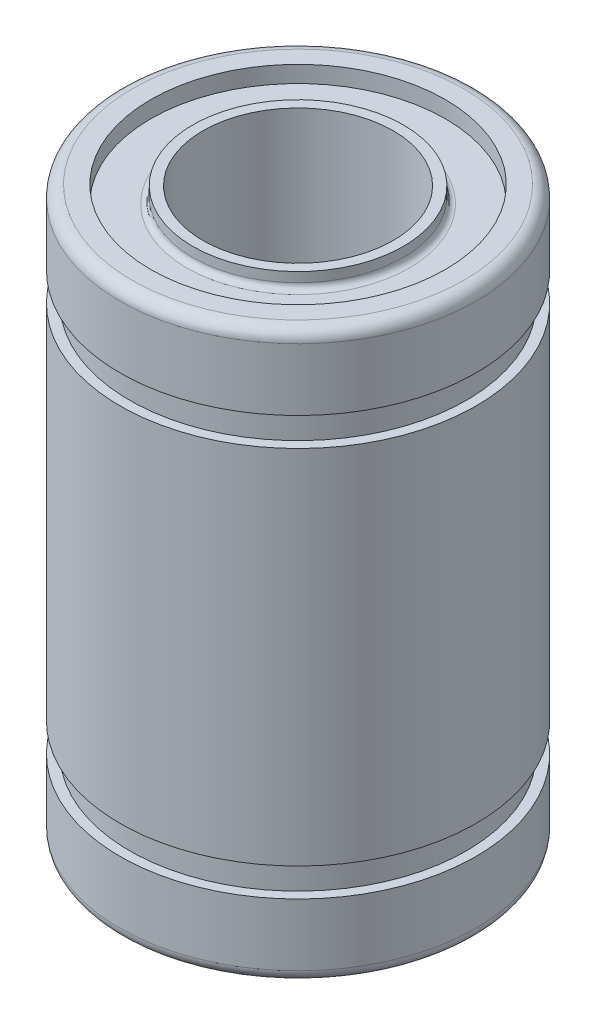
SolidWorks part; units mm, degrees
ref_plane "Front Plane" through (0, 0, 0) normal (0, 0, 1) x (1, 0, 0)
ref_plane "Top Plane" through (0, 0, 0) normal (0, 1, 0) x (1, 0, 0)
ref_plane "Right Plane" through (0, 0, 0) normal (1, 0, 0) x (0, 0, -1)
sketch "Sketch1" plane through (0, 0, 0) normal (0, 0, 1) x (1, 0, 0)
  line L0 (4.425, 11.8804) -> (4, 11.8804)
  line L1 (4, 11.8804) -> (4, -11.8804)
  line L2 (4, -11.8804) -> (4.425, -11.8804)
  line L3 (4.425, -11.8804) -> (4.425, -11.474)
  line L4 (4.679, -11.22) -> (6.19, -11.22)
  line L5 (6.19, -11.22) -> (6.19, -11.92)
  line L6 (6.19, -11.92) -> (6.972, -11.92)
  line L7 (7.48, -11.412) -> (7.48, -8.8)
  line L8 (7.48, -8.8) -> (7.075, -8.8)
  line L9 (7.075, -8.8) -> (7.075, -7.6)
  line L10 (7.075, -7.6) -> (7.48, -7.6)
  line L11 (7.48, -7.6) -> (7.48, 7.6)
  line L12 (7.48, 7.6) -> (7.075, 7.6)
  line L13 (7.075, 7.6) -> (7.075, 8.8)
  line L14 (7.075, 8.8) -> (7.48, 8.8)
  line L15 (7.48, 8.8) -> (7.48, 11.412)
  line L16 (6.972, 11.92) -> (6.19, 11.92)
  line L17 (6.19, 11.92) -> (6.19, 11.22)
  line L18 (6.19, 11.22) -> (4.679, 11.22)
  line L19 (4.425, 11.474) -> (4.425, 11.8804)
  line L20 (0, 11.9213) -> (0, -11.9213) construction
  arc A0 (4.425, -11.474) -> (4.679, -11.22) centre (4.679, -11.474) cw
  arc A1 (6.972, -11.92) -> (7.48, -11.412) centre (6.972, -11.412) ccw
  arc A2 (7.48, 11.412) -> (6.972, 11.92) centre (6.972, 11.412) ccw
  arc A3 (4.679, 11.22) -> (4.425, 11.474) centre (4.679, 11.474) cw
revolve "Revolve1" add sketch "Sketch1" angle 360 about L20
